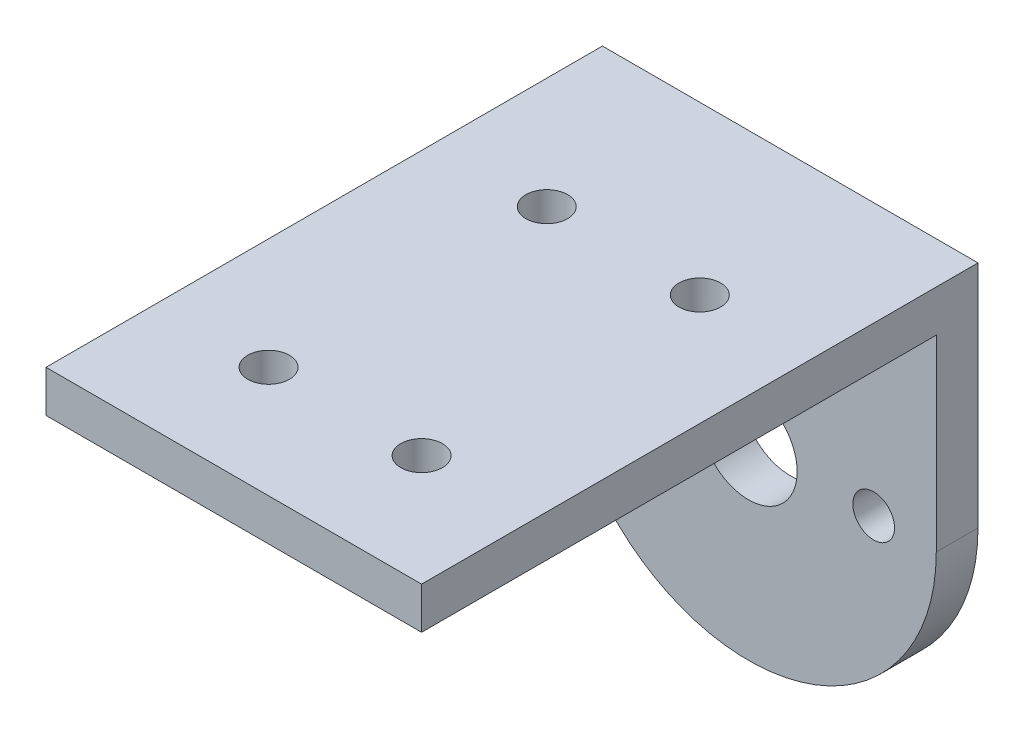
SolidWorks part; units mm, degrees
ref_plane "前视基准面" through (0, 0, 0) normal (0, 0, 1) x (1, 0, 0)
ref_plane "上视基准面" through (0, 0, 0) normal (0, 1, 0) x (1, 0, 0)
ref_plane "右视基准面" through (0, 0, 0) normal (1, 0, 0) x (0, 0, -1)
sketch "Model" plane through (0, 0, 0) normal (0, 0, 1) x (1, 0, 0)
  line L0 (2619.7667, 1592.8264) -> (2619.7667, 1609.3264)
  line L1 (2592.7667, 1592.8264) -> (2592.7667, 1609.3264)
  line L2 (2592.7667, 1609.3264) -> (2619.7667, 1609.3264)
  circle A0 centre (2606.2667, 1592.8264) radius 3.5
  arc A1 (2592.7667, 1592.8264) -> (2619.7667, 1592.8264) centre (2606.2667, 1592.8264) ccw
  dimension "D1" = 16.5
extrude "凸台-拉伸1" add sketch "Model" along normal blind 40
sketch "草图3" plane through (2619.7667, 0, 0) normal (1, 0, 0) x (0, 0, -1)
  line L0 (-40, 1592.8264) -> (-40, 1609.3264) construction
  line L1 (-40, 1606.3264) -> (-3, 1606.3264)
  line L2 (-40, 1606.3264) -> (-40, 1569.3264)
  line L3 (-40, 1569.3264) -> (-3, 1569.3264)
  line L4 (-3, 1606.3264) -> (-3, 1569.3264)
  line L5 (-40, 1609.3264) -> (0, 1609.3264) construction
  line L6 (0, 1592.8264) -> (0, 1609.3264) construction
  dimension "D1" = 3
  dimension "D2" = 3
  dimension "D3" = 40
extrude "切除-拉伸1" cut sketch "草图3" against normal blind 36.778
sketch "草图4" plane through (0, 1609.3264, 0) normal (0, 1, 0) x (1, 0, 0)
  line L6 (2619.7667, -40) -> (2619.7667, -32)
  circle A0 centre (2600.7667, -32) radius 1.5
  circle A1 centre (2611.7667, -32) radius 1.5
  circle A2 centre (2600.7667, -12) radius 1.5
  circle A3 centre (2611.7667, -12) radius 1.5
  dimension "D7" = 3
  dimension "D8" = 3
  dimension "D9" = 3
  dimension "D10" = 3
extrude "切除-拉伸2" cut sketch "草图4" against normal blind 40 contours A0 | A1 | A3 | A2
sketch "Sketch1" plane through (0, 0, 0) normal (0, 0, -1) x (-1, 0, 0)
  circle A1 centre (-2615.2667, 1592.8264) radius 1.5
  circle A2 centre (-2597.2667, 1592.8264) radius 1.5
  dimension "D2" = 3
  dimension "D4" = 3
extrude "Cut-Extrude2" cut sketch "Sketch1" against normal blind 29 contours A2 | A1
